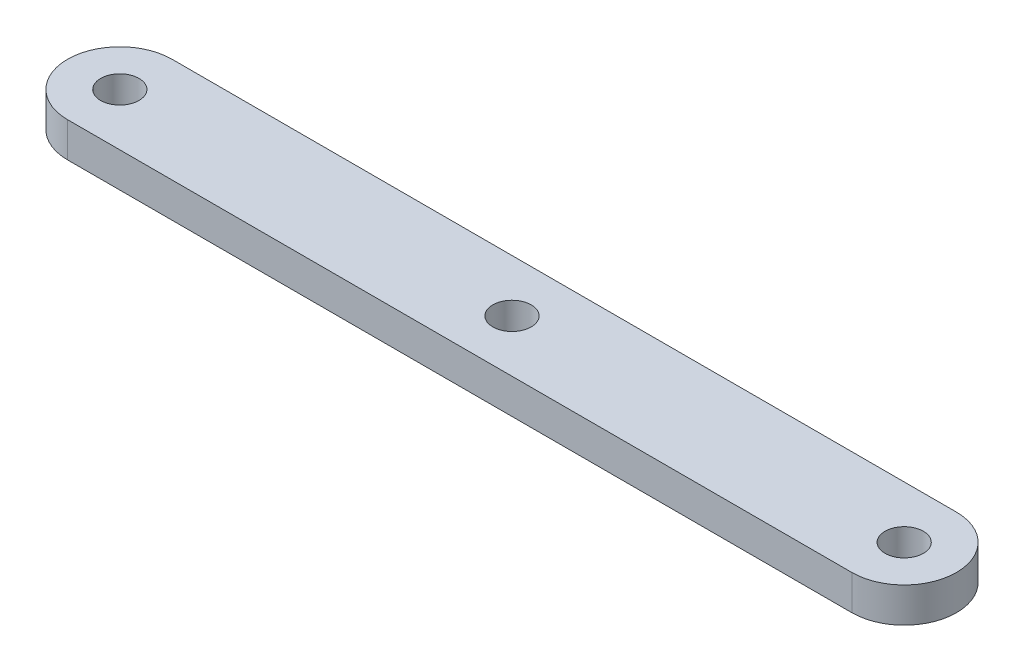
SolidWorks part; units mm, degrees
ref_plane "正面" through (0, 0, 0) normal (0, 0, 1) x (1, 0, 0)
ref_plane "平面" through (0, 0, 0) normal (0, 1, 0) x (1, 0, 0)
ref_plane "右側面" through (0, 0, 0) normal (1, 0, 0) x (0, 0, -1)
sketch "ｽｹｯﾁ1" plane through (0, 0, 0) normal (0, 1, 0) x (1, 0, 0)
  line L0 (0, 0) -> (45, 0) construction
  line L1 (0, 3) -> (45, 3)
  line L2 (0, -3) -> (45, -3)
  arc A0 (0, 3) -> (0, -3) centre (0, 0) ccw
  arc A1 (45, -3) -> (45, 3) centre (45, 0) ccw
  point P3 (22.5, 0)
  point P8 (0, 0)
  dimension "D2" = 3
  dimension "D1" = 45
extrude "ﾎﾞｽ - 押し出し1" add sketch "ｽｹｯﾁ1" along normal blind 2
sketch "ｽｹｯﾁ2" plane through (0, 2, 0) normal (0, 1, 0) x (1, 0, 0)
  line L0 (22.5, 3) -> (22.5, -3) construction
  line L1 (45, 3) -> (0, 3) construction
  line L2 (0, -3) -> (45, -3) construction
  circle A0 centre (0, 0) radius 1.1
  circle A1 centre (45, 0) radius 1.1
  circle A2 centre (22.5, 0) radius 1.1
  dimension "D1" = 2.2
extrude "ｶｯﾄ - 押し出し1" cut sketch "ｽｹｯﾁ2" against normal through all
